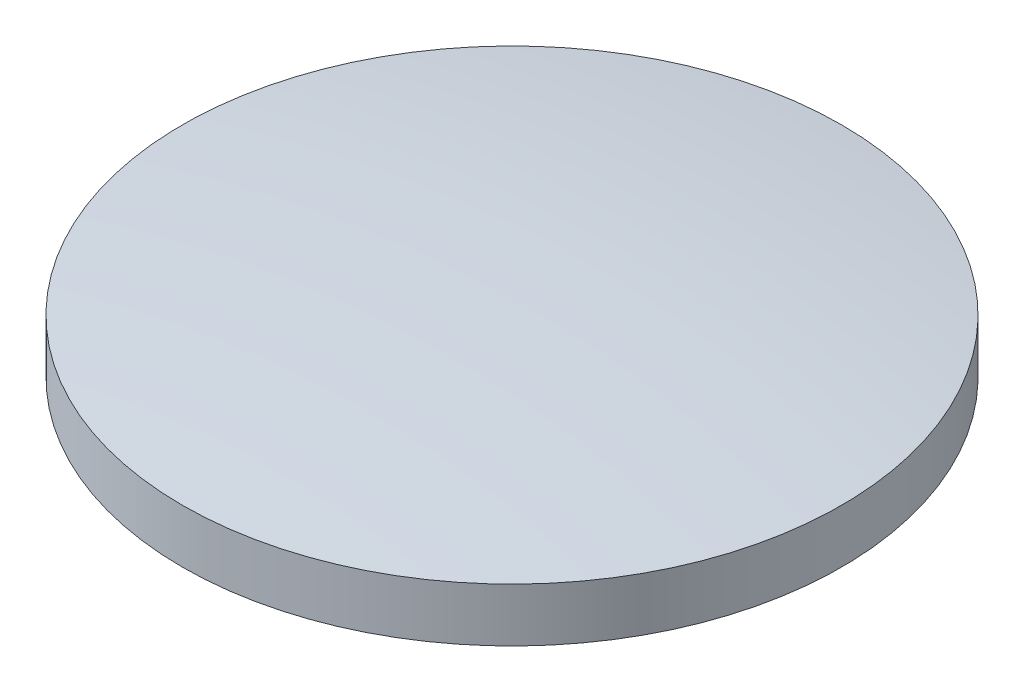
SolidWorks part; units mm, degrees
ref_plane "Front" through (0, 0, 0) normal (0, 0, 1) x (1, 0, 0)
ref_plane "Top" through (0, 0, 0) normal (0, 1, 0) x (1, 0, 0)
ref_plane "Right" through (0, 0, 0) normal (1, 0, 0) x (0, 0, -1)
sketch "Sketch1" plane through (0, 0, 0) normal (0, 0, 1) x (1, 0, 0)
  line L0 (45.5, -5.3526) -> (45.5, -12.7526)
  line L1 (45.5, -12.7526) -> (0, -12.7526)
  line L3 (0, -12.7526) -> (0, -2.2526)
  arc A0 (0, -2.2526) -> (45.5, -5.3526) centre (0.2358, -334.2525) cw
  dimension "D4" = 332
  dimension "D1" = 7.4
  dimension "D2" = 10.5
  dimension "D3" = 45.5
revolve "Revolve1" add sketch "Sketch1" angle 360 about L3
